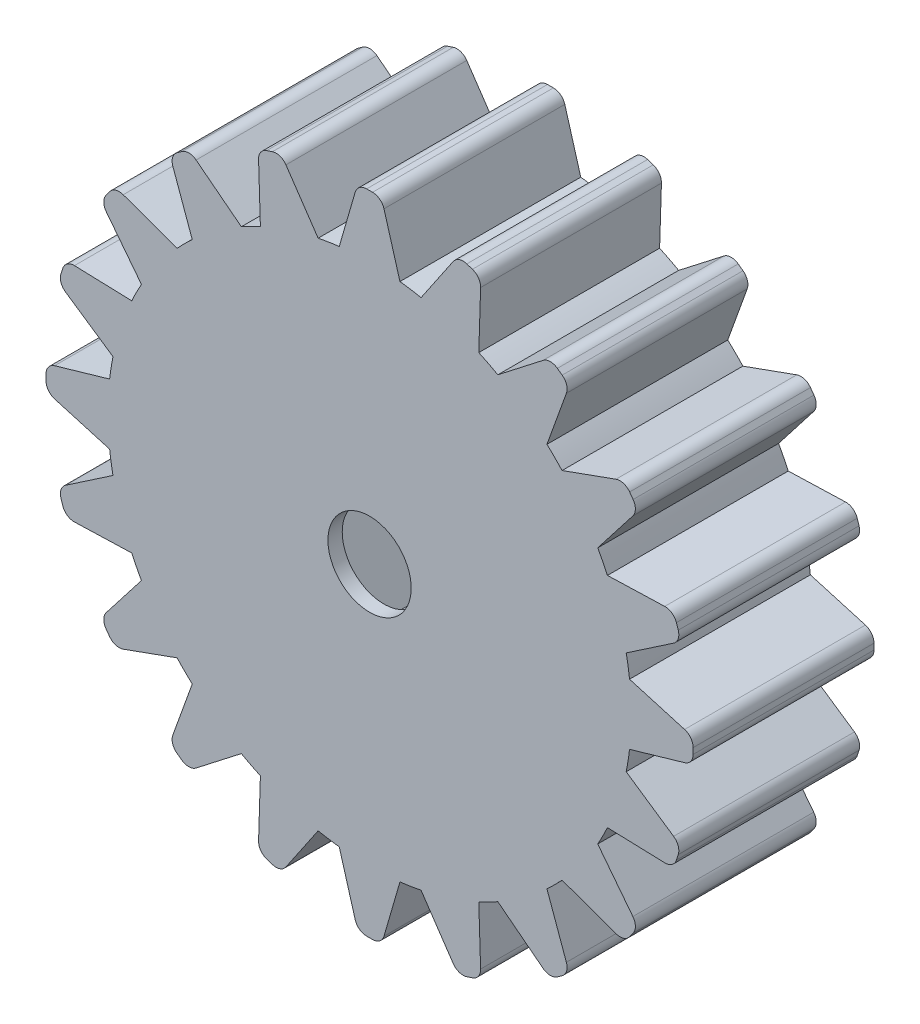
SolidWorks part; units mm, degrees
ref_plane "Front Plane" through (0, 0, 0) normal (0, 0, 1) x (1, 0, 0)
ref_plane "Top Plane" through (0, 0, 0) normal (0, 1, 0) x (1, 0, 0)
ref_plane "Right Plane" through (0, 0, 0) normal (1, 0, 0) x (0, 0, -1)
sketch "Sketch1" plane through (0, 0, 0) normal (0, 0, 1) x (1, 0, 0)
  line L0 (0, 0) -> (0, 6.9703) construction
  line L1 (-0.1245, 13.6) -> (0.1245, 13.6)
  line L2 (-0.6047, 13.2393) -> (-1.276, 10.9257)
  line L3 (0.6047, 13.2393) -> (1.276, 10.9257)
  line L4 (3.5161, 12.7782) -> (2.1627, 10.7853)
  line L5 (4.0843, 12.9728) -> (4.321, 12.8959)
  line L6 (4.6662, 12.4045) -> (4.5898, 9.9967)
  line L7 (7.2927, 11.0663) -> (5.3897, 9.5891)
  line L8 (7.8932, 11.0758) -> (8.0946, 10.9295)
  line L9 (8.2711, 10.3554) -> (7.4543, 8.0891)
  line L10 (10.3554, 8.2711) -> (8.0891, 7.4543)
  line L11 (10.9295, 8.0946) -> (11.0758, 7.8932)
  line L12 (11.0663, 7.2927) -> (9.5891, 5.3897)
  line L13 (12.4045, 4.6662) -> (9.9967, 4.5898)
  line L14 (12.8959, 4.321) -> (12.9728, 4.0843)
  line L15 (12.7782, 3.5161) -> (10.7853, 2.1627)
  line L16 (13.2393, 0.6047) -> (10.9257, 1.276)
  line L17 (13.6, 0.1245) -> (13.6, -0.1245)
  line L18 (13.2393, -0.6047) -> (10.9257, -1.276)
  line L19 (12.7782, -3.5161) -> (10.7853, -2.1627)
  line L20 (12.9728, -4.0843) -> (12.8959, -4.321)
  line L21 (12.4045, -4.6662) -> (9.9967, -4.5898)
  line L22 (11.0663, -7.2927) -> (9.5891, -5.3897)
  line L23 (11.0758, -7.8932) -> (10.9295, -8.0946)
  line L24 (10.3554, -8.2711) -> (8.0891, -7.4543)
  line L25 (8.2711, -10.3554) -> (7.4543, -8.0891)
  line L26 (8.0946, -10.9295) -> (7.8932, -11.0758)
  line L27 (7.2927, -11.0663) -> (5.3897, -9.5891)
  line L28 (4.6662, -12.4045) -> (4.5898, -9.9967)
  line L29 (4.321, -12.8959) -> (4.0843, -12.9728)
  line L30 (3.5161, -12.7782) -> (2.1627, -10.7853)
  line L31 (0.6047, -13.2393) -> (1.276, -10.9257)
  line L32 (0.1245, -13.6) -> (-0.1245, -13.6)
  line L33 (-0.6047, -13.2393) -> (-1.276, -10.9257)
  line L34 (-3.5161, -12.7782) -> (-2.1627, -10.7853)
  line L35 (-4.0843, -12.9728) -> (-4.321, -12.8959)
  line L36 (-4.6662, -12.4045) -> (-4.5898, -9.9967)
  line L37 (-7.2927, -11.0663) -> (-5.3897, -9.5891)
  line L38 (-7.8932, -11.0758) -> (-8.0946, -10.9295)
  line L39 (-8.2711, -10.3554) -> (-7.4543, -8.0891)
  line L40 (-10.3554, -8.2711) -> (-8.0891, -7.4543)
  line L41 (-10.9295, -8.0946) -> (-11.0758, -7.8932)
  line L42 (-11.0663, -7.2927) -> (-9.5891, -5.3897)
  line L43 (-12.4045, -4.6662) -> (-9.9967, -4.5898)
  line L44 (-12.8959, -4.321) -> (-12.9728, -4.0843)
  line L45 (-12.7782, -3.5161) -> (-10.7853, -2.1627)
  line L46 (-13.2393, -0.6047) -> (-10.9257, -1.276)
  line L47 (-13.6, -0.1245) -> (-13.6, 0.1245)
  line L48 (-13.2393, 0.6047) -> (-10.9257, 1.276)
  line L49 (-12.7782, 3.5161) -> (-10.7853, 2.1627)
  line L50 (-12.9728, 4.0843) -> (-12.8959, 4.321)
  line L51 (-12.4045, 4.6662) -> (-9.9967, 4.5898)
  line L52 (-11.0663, 7.2927) -> (-9.5891, 5.3897)
  line L53 (-11.0758, 7.8932) -> (-10.9295, 8.0946)
  line L54 (-10.3554, 8.2711) -> (-8.0891, 7.4543)
  line L55 (-8.2711, 10.3554) -> (-7.4543, 8.0891)
  line L56 (-8.0946, 10.9295) -> (-7.8932, 11.0758)
  line L57 (-7.2927, 11.0663) -> (-5.3897, 9.5891)
  line L58 (-4.6662, 12.4045) -> (-4.5898, 9.9967)
  line L59 (-4.321, 12.8959) -> (-4.0843, 12.9728)
  line L60 (-3.5161, 12.7782) -> (-2.1627, 10.7853)
  arc A0 (2.1627, 10.7853) -> (1.276, 10.9257) centre (0, 0) ccw
  arc A1 (0.1245, 13.6) -> (0.6047, 13.2393) centre (0.1245, 13.1) cw
  arc A2 (-0.1245, 13.6) -> (-0.6047, 13.2393) centre (-0.1245, 13.1) ccw
  arc A3 (4.0843, 12.9728) -> (3.5161, 12.7782) centre (3.9298, 12.4973) ccw
  arc A4 (4.321, 12.8959) -> (4.6662, 12.4045) centre (4.1665, 12.4204) cw
  arc A5 (7.8932, 11.0758) -> (7.2927, 11.0663) centre (7.5993, 10.6713) ccw
  arc A6 (8.0946, 10.9295) -> (8.2711, 10.3554) centre (7.8007, 10.525) cw
  arc A7 (10.9295, 8.0946) -> (10.3554, 8.2711) centre (10.525, 7.8007) ccw
  arc A8 (11.0758, 7.8932) -> (11.0663, 7.2927) centre (10.6713, 7.5993) cw
  arc A9 (12.8959, 4.321) -> (12.4045, 4.6662) centre (12.4204, 4.1665) ccw
  arc A10 (12.9728, 4.0843) -> (12.7782, 3.5161) centre (12.4973, 3.9298) cw
  arc A11 (13.6, 0.1245) -> (13.2393, 0.6047) centre (13.1, 0.1245) ccw
  arc A12 (13.6, -0.1245) -> (13.2393, -0.6047) centre (13.1, -0.1245) cw
  arc A13 (12.9728, -4.0843) -> (12.7782, -3.5161) centre (12.4973, -3.9298) ccw
  arc A14 (12.8959, -4.321) -> (12.4045, -4.6662) centre (12.4204, -4.1665) cw
  arc A15 (11.0758, -7.8932) -> (11.0663, -7.2927) centre (10.6713, -7.5993) ccw
  arc A16 (10.9295, -8.0946) -> (10.3554, -8.2711) centre (10.525, -7.8007) cw
  arc A17 (8.0946, -10.9295) -> (8.2711, -10.3554) centre (7.8007, -10.525) ccw
  arc A18 (7.8932, -11.0758) -> (7.2927, -11.0663) centre (7.5993, -10.6713) cw
  arc A19 (4.321, -12.8959) -> (4.6662, -12.4045) centre (4.1665, -12.4204) ccw
  arc A20 (4.0843, -12.9728) -> (3.5161, -12.7782) centre (3.9298, -12.4973) cw
  arc A21 (0.1245, -13.6) -> (0.6047, -13.2393) centre (0.1245, -13.1) ccw
  arc A22 (-0.1245, -13.6) -> (-0.6047, -13.2393) centre (-0.1245, -13.1) cw
  arc A23 (-4.0843, -12.9728) -> (-3.5161, -12.7782) centre (-3.9298, -12.4973) ccw
  arc A24 (-4.321, -12.8959) -> (-4.6662, -12.4045) centre (-4.1665, -12.4204) cw
  arc A25 (-7.8932, -11.0758) -> (-7.2927, -11.0663) centre (-7.5993, -10.6713) ccw
  arc A26 (-8.0946, -10.9295) -> (-8.2711, -10.3554) centre (-7.8007, -10.525) cw
  arc A27 (-10.9295, -8.0946) -> (-10.3554, -8.2711) centre (-10.525, -7.8007) ccw
  arc A28 (-11.0758, -7.8932) -> (-11.0663, -7.2927) centre (-10.6713, -7.5993) cw
  arc A29 (-12.8959, -4.321) -> (-12.4045, -4.6662) centre (-12.4204, -4.1665) ccw
  arc A30 (-12.9728, -4.0843) -> (-12.7782, -3.5161) centre (-12.4973, -3.9298) cw
  arc A31 (-13.6, -0.1245) -> (-13.2393, -0.6047) centre (-13.1, -0.1245) ccw
  arc A32 (-13.6, 0.1245) -> (-13.2393, 0.6047) centre (-13.1, 0.1245) cw
  arc A33 (-12.9728, 4.0843) -> (-12.7782, 3.5161) centre (-12.4973, 3.9298) ccw
  arc A34 (-12.8959, 4.321) -> (-12.4045, 4.6662) centre (-12.4204, 4.1665) cw
  arc A35 (-11.0758, 7.8932) -> (-11.0663, 7.2927) centre (-10.6713, 7.5993) ccw
  arc A36 (-10.9295, 8.0946) -> (-10.3554, 8.2711) centre (-10.525, 7.8007) cw
  arc A37 (-8.0946, 10.9295) -> (-8.2711, 10.3554) centre (-7.8007, 10.525) ccw
  arc A38 (-7.8932, 11.0758) -> (-7.2927, 11.0663) centre (-7.5993, 10.6713) cw
  arc A39 (-4.321, 12.8959) -> (-4.6662, 12.4045) centre (-4.1665, 12.4204) ccw
  arc A40 (-4.0843, 12.9728) -> (-3.5161, 12.7782) centre (-3.9298, 12.4973) cw
  arc A41 (-1.276, 10.9257) -> (-2.1627, 10.7853) centre (0, 0) ccw
  arc A42 (-4.5898, 9.9967) -> (-5.3897, 9.5891) centre (0, 0) ccw
  arc A43 (-7.4543, 8.0891) -> (-8.0891, 7.4543) centre (0, 0) ccw
  arc A44 (-9.5891, 5.3897) -> (-9.9967, 4.5898) centre (0, 0) ccw
  arc A45 (-10.7853, 2.1627) -> (-10.9257, 1.276) centre (0, 0) ccw
  arc A46 (-10.9257, -1.276) -> (-10.7853, -2.1627) centre (0, 0) ccw
  arc A47 (-9.9967, -4.5898) -> (-9.5891, -5.3897) centre (0, 0) ccw
  arc A48 (-8.0891, -7.4543) -> (-7.4543, -8.0891) centre (0, 0) ccw
  arc A49 (-5.3897, -9.5891) -> (-4.5898, -9.9967) centre (0, 0) ccw
  arc A50 (-2.1627, -10.7853) -> (-1.276, -10.9257) centre (0, 0) ccw
  arc A51 (1.276, -10.9257) -> (2.1627, -10.7853) centre (0, 0) ccw
  arc A52 (4.5898, -9.9967) -> (5.3897, -9.5891) centre (0, 0) ccw
  arc A53 (7.4543, -8.0891) -> (8.0891, -7.4543) centre (0, 0) ccw
  arc A54 (9.5891, -5.3897) -> (9.9967, -4.5898) centre (0, 0) ccw
  arc A55 (10.7853, -2.1627) -> (10.9257, -1.276) centre (0, 0) ccw
  arc A56 (10.9257, 1.276) -> (10.7853, 2.1627) centre (0, 0) ccw
  arc A57 (9.9967, 4.5898) -> (9.5891, 5.3897) centre (0, 0) ccw
  arc A58 (8.0891, 7.4543) -> (7.4543, 8.0891) centre (0, 0) ccw
  arc A59 (5.3897, 9.5891) -> (4.5898, 9.9967) centre (0, 0) ccw
  point P7 (0, 13.6)
  point P12 (0.5, 13.6)
  point P15 (-0.5, 13.6)
  point P170 (0, 0)
  dimension "D1" = 22
  dimension "D4" = 0.5
  dimension "D2" = 13.6
  dimension "D3" = 1
  dimension "D5" = 20
extrude "Boss-Extrude1" add sketch "Sketch1" along normal blind 7.6
sketch "Sketch4" plane through (0, 0, 0) normal (0, 0, -1) x (-1, 0, 0)
  line L6 (-6.9264, -0.1594) -> (-3.3251, -6.0781)
  line L7 (-3.3251, -6.0781) -> (3.6013, -5.9187)
  line L8 (3.6013, -5.9187) -> (6.9264, 0.1594)
  line L9 (6.9264, 0.1594) -> (3.3251, 6.0781)
  line L10 (3.3251, 6.0781) -> (-3.6013, 5.9187)
  line L11 (-3.6013, 5.9187) -> (-6.9264, -0.1594)
  circle A0 centre (0, 0) radius 1.75
  point P6 (0, 0)
extrude "Cut-Extrude1" cut sketch "Sketch4" against normal blind 7
sketch "Sketch5" plane through (0, 0, 0) normal (0, 0, -1) x (-1, 0, 0)
  circle A0 centre (0, 0) radius 1.75
  point P3 (0, 0)
  point P4 (0, 0)
  dimension "D1" = 3.5
extrude "Cut-Extrude2" cut sketch "Sketch5" against normal through all
